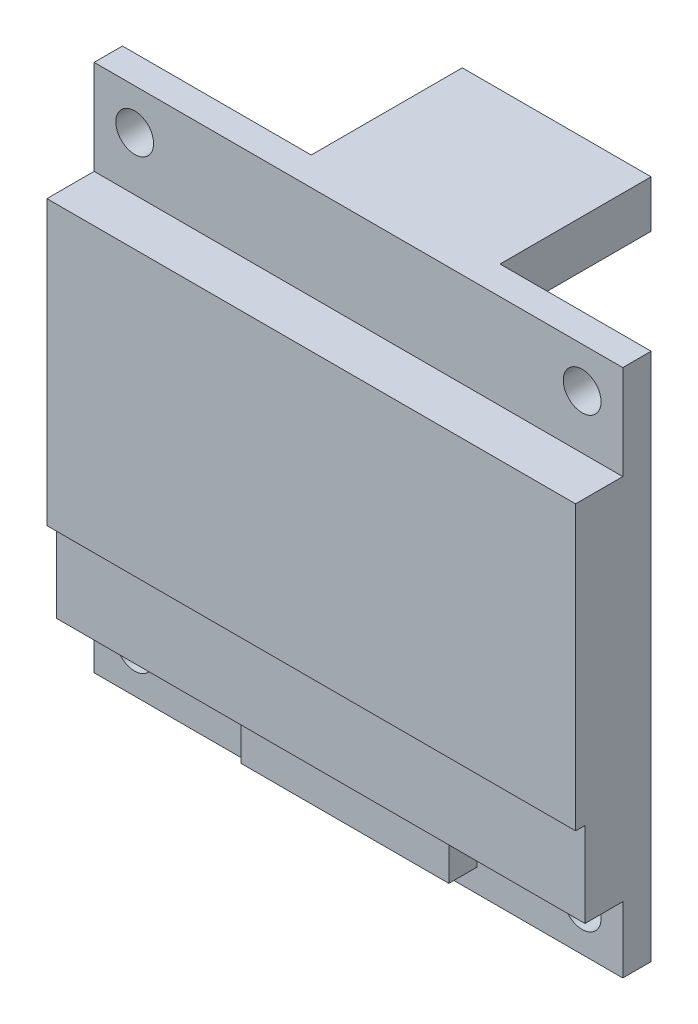
SolidWorks part; units mm, degrees
ref_plane "Спереди" through (0, 0, 0) normal (0, 0, 1) x (1, 0, 0)
ref_plane "Сверху" through (0, 0, 0) normal (0, 1, 0) x (1, 0, 0)
ref_plane "Справа" through (0, 0, 0) normal (1, 0, 0) x (0, 0, -1)
sketch "Эскиз1" plane through (0, 0, 0) normal (0, 0, 1) x (1, 0, 0)
  line L1 (0, 0) -> (28, 0)
  line L2 (0, 0) -> (0, 28)
  line L3 (0, 28) -> (28, 28)
  line L4 (28, 0) -> (28, 28)
extrude "Бобышка-Вытянуть3" add sketch "Эскиз1" along normal blind 1.5
sketch "Эскиз3" plane through (0, 0, 1.5) normal (0, 0, 1) x (1, 0, 0)
  line L0 (0, 28) -> (0, 0) construction
  line L1 (0, 23) -> (28, 23)
  line L2 (0, 23) -> (0, 3.5)
  line L3 (0, 3.5) -> (28, 3.5)
  line L4 (28, 23) -> (28, 3.5)
  line L5 (28, 0) -> (28, 28) construction
  dimension "D1" = 19.5
  dimension "D2" = 5
extrude "Бобышка-Вытянуть4" add sketch "Эскиз3" along normal blind 2
sketch "Эскиз5" plane through (0, 0, 3.5) normal (0, 0, 1) x (1, 0, 0)
  line L0 (28, 3.5) -> (28, 23) construction
  line L1 (0, 23) -> (28, 23)
  line L2 (0, 23) -> (0, 8)
  line L3 (0, 8) -> (28, 8)
  line L4 (28, 23) -> (28, 8)
extrude "Бобышка-Вытянуть5" add sketch "Эскиз5" along normal blind 0.5
sketch "Эскиз6" plane through (0, 0, 1.5) normal (0, 0, 1) x (1, 0, 0)
  line L0 (0, 3.5) -> (28, 3.5) construction
  line L1 (9.2875, 3.5) -> (20.2875, 3.5)
  line L2 (9.2875, 3.5) -> (9.2875, 1.2336)
  line L3 (9.2875, 1.2336) -> (20.2875, 1.2336)
  line L4 (20.2875, 3.5) -> (20.2875, 1.2336)
  line M5 (28, 3.5) -> (0, 3.5)
extrude "Бобышка-Вытянуть6" add sketch "Эскиз6" along normal blind 1.5 contours L4 L2 L3 M5
sketch "Эскиз7" plane through (0, 0, 1.5) normal (0, 0, 1) x (1, 0, 0)
  line L0 (26.85, 25.85) -> (24.85, 25.85) construction
  line L1 (25.85, 26.85) -> (25.85, 24.85) construction
  line L2 (3.15, 25.85) -> (1.15, 25.85) construction
  line L3 (2.15, 26.85) -> (2.15, 24.85) construction
  line L4 (2.15, 3.15) -> (2.15, 1.15) construction
  line L5 (1.15, 2.15) -> (3.15, 2.15) construction
  line L6 (24.85, 2.15) -> (26.85, 2.15) construction
  line L7 (25.85, 3.15) -> (25.85, 1.15) construction
  line L8 (0, 3.5) -> (0, 0) construction
  line L9 (0, 0) -> (28, 0) construction
  circle A0 centre (2.15, 2.15) radius 1
  circle A1 centre (2.15, 25.85) radius 1
  circle A2 centre (25.85, 25.85) radius 1
  circle A3 centre (25.85, 2.15) radius 1
  point P24 (0, 0)
  dimension "D1" = 23.7
  dimension "D3" = 2
  dimension "D5" = 2
  dimension "D4" = 2
  dimension "D6" = 2
  dimension "D2" = 23.7
  dimension "D7" = 2.15
  dimension "D8" = 2.15
extrude "Вырез-Вытянуть4" cut sketch "Эскиз7" against normal blind 1.5
sketch "Эскиз10" plane through (0, 0, 0) normal (0, 0, -1) x (-1, 0, 0)
  line L0 (-28, 28) -> (0, 28) construction
  line L1 (-20, 28) -> (-10, 28)
  line L2 (-20, 28) -> (-20, 25.5)
  line L3 (-20, 25.5) -> (-10, 25.5)
  line L4 (-10, 28) -> (-10, 25.5)
  dimension "D1" = 10
  dimension "D2" = 2.5
  dimension "D3" = 8
extrude "Бобышка-Вытянуть8" add sketch "Эскиз10" along normal blind 8
